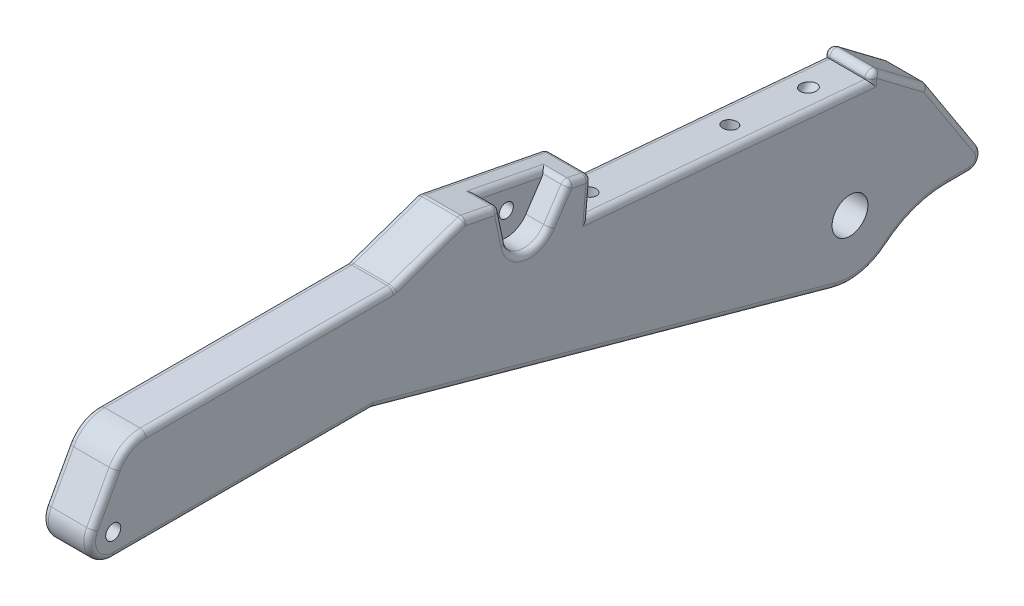
SolidWorks part; units mm, degrees
ref_plane "Front Plane" through (0, 0, 0) normal (0, 0, 1) x (1, 0, 0)
ref_plane "Top Plane" through (0, 0, 0) normal (0, 1, 0) x (1, 0, 0)
ref_plane "Right Plane" through (0, 0, 0) normal (1, 0, 0) x (0, 0, -1)
sketch "Sketch1" plane through (0, 0, 0) normal (1, 0, 0) x (0, 0, -1)
  line L0 (-5.5746, 3.0408) -> (3.158, 19.05)
  line L1 (3.158, 19.05) -> (75.6627, 19.05)
  line L3 (129.0542, 18.9233) -> (128.2241, 9.4345)
  line L4 (128.2241, 9.4345) -> (204.1341, 2.7933)
  line L6 (0, -6.35) -> (69.85, -6.35)
  line L8 (-5.5746, 3.0408) -> (7.9306, 27.7995) construction
  line L9 (129.0542, 18.9233) -> (94.7762, 25.6144)
  line L10 (94.7762, 25.6144) -> (75.6627, 19.05)
  line L12 (70.0006, 30.4506) -> (127.6524, 19.1969) construction
  line L15 (128.3624, 11.016) -> (128.9159, 17.3418) construction
  line L24 (219.6164, -5.5196) -> (233.4447, -26.8477) construction
  line L26 (219.7687, -5.7545) -> (233.4447, -26.8477)
  line L29 (69.85, 30.48) -> (129.0542, 18.9233) construction
  line L30 (206.6988, 4.2294) -> (219.393, -5.351) construction
  line L31 (204.1341, 2.7933) -> (204.161, 3.1007) construction
  line L32 (230.7807, -31.75) -> (224.8967, -31.75) construction
  line L33 (194.299, -40.7027) -> (69.85, -6.35) construction
  line L34 (206.6988, 4.2294) -> (219.393, -5.351)
  line L35 (204.1341, 2.7933) -> (204.161, 3.1007)
  line L36 (230.7807, -31.75) -> (224.8967, -31.75)
  line L37 (194.299, -40.7027) -> (69.85, -6.35)
  line L39 (-5.5746, 3.0408) -> (7.9306, 27.7995) construction
  circle A0 centre (0, 0) radius 2.032
  arc A1 (-5.5746, 3.0408) -> (0, -6.35) centre (0, 0) ccw
  arc A3 (0, -6.35) -> (-5.5746, 3.0408) centre (0, 0) ccw construction
  arc A12 (230.7807, -31.75) -> (233.4447, -26.8477) centre (230.7807, -28.575) ccw construction
  arc A13 (230.7807, -31.75) -> (233.4447, -26.8477) centre (230.7807, -28.575) ccw
  arc A14 (206.6988, 4.2294) -> (204.161, 3.1007) centre (205.7425, 2.9623) ccw construction
  arc A15 (224.8967, -31.75) -> (208.6668, -37.6115) centre (224.8967, -57.15) ccw construction
  arc A16 (194.299, -40.7027) -> (208.6668, -37.6115) centre (198.5232, -25.4) ccw construction
  arc A17 (206.6988, 4.2294) -> (204.161, 3.1007) centre (205.7425, 2.9623) ccw
  arc A18 (224.8967, -31.75) -> (208.6668, -37.6115) centre (224.8967, -57.15) ccw
  arc A19 (194.299, -40.7027) -> (208.6668, -37.6115) centre (198.5232, -25.4) ccw
  arc A20 (219.7687, -5.7545) -> (219.393, -5.351) centre (218.4366, -6.6181) ccw construction
  arc A21 (219.7687, -5.7545) -> (219.393, -5.351) centre (218.4366, -6.6181) ccw
  dimension "D1" = 4.064
  dimension "D2" = 19.05
  dimension "D3" = 30
  dimension "D4" = 34.925
extrude "Boss-Extrude1" add sketch "Sketch1" along normal blind 12.7
fillet "Fillet1" radius 9.525 1 edges at (6.35, 19.05, -3.158)
sketch "Sketch2" plane through (0, 0, 0) normal (-1, 0, 0) x (0, 0, 1)
  circle A0 centre (-198.5232, -25.4) radius 4.826
  circle A3 centre (-198.5232, -25.4) radius 5.715 construction
  dimension "D1" = 9.652
extrude "Cut-Extrude1" cut sketch "Sketch2" against normal through all
sketch "Sketch9" plane through (12.7, 0, 0) normal (1, 0, 0) x (0, 0, -1)
  line L0 (106.0359, 14.4582) -> (104.1247, 23.7895)
  line L2 (117.5418, 12.2123) -> (122.8219, 20.1398)
  line L3 (104.1247, 23.7895) -> (122.8219, 20.1398)
  line L4 (129.0542, 18.9233) -> (94.7762, 25.6144) construction
  arc A0 (106.0359, 14.4582) -> (117.5418, 12.2123) centre (112.2567, 15.7323) ccw
  dimension "D1" = 12.7
  dimension "D2" = 6.35
  dimension "D3" = 19.05
extrude "Cut-Extrude6" cut sketch "Sketch9" against normal blind 6.35
sketch "Sketch10" plane through (6.35, 0, 0) normal (1, 0, 0) x (0, 0, -1)
  circle A0 centre (112.2567, 15.7323) radius 1.905
  arc A1 (106.0359, 14.4582) -> (117.5418, 12.2123) centre (112.2567, 15.7323) ccw construction
  dimension "D1" = 3.81
extrude "Cut-Extrude7" cut sketch "Sketch10" against normal through all
sketch "Sketch4" plane through (0, 0, 0) normal (1, 0, 0) x (0, 0, -1)
  circle A0 centre (198.5232, -25.4) radius 5.715
  dimension "D1" = 11.43
extrude "Cut-Extrude2" cut sketch "Sketch4" along normal blind 1.5875
fillet "Fillet2" radius 1.5875 48 edges at (0, 2.947, -204.1476) (0, 4.4128, -205.0973) (0, -0.5608, -213.0459) (0, -5.5363, -219.5985) (0, -16.3011, -226.6067) (0, -30.091, -233.5704) (0, -31.75, -227.8387) (0, -33.2603, -216.2687) (0, -40.9199, -201.8622) (0, -6.35, -34.925) (0, -3.2414, 5.4604) (0, 8.5635, 2.5621) (0, 17.7156, -3.9501) (12.7, 2.947, -204.1476) (12.7, 4.4128, -205.0973) (12.7, -0.5608, -213.0459) (12.7, -5.5363, -219.5985) (12.7, -16.3011, -226.6067) (12.7, -30.091, -233.5704) (12.7, -31.75, -227.8387) (12.7, -33.2603, -216.2687) (12.7, -40.9199, -201.8622) (12.7, -6.35, -34.925) (12.7, -3.2414, 5.4604) (12.7, 8.5635, 2.5621) (12.7, 17.7156, -3.9501) (0, -23.5263, -132.0745) (0, 6.1139, -166.1791) (0, 14.1789, -128.6392) (0, 19.05, -42.2375) (12.7, -23.5263, -132.0745) (12.7, 6.1139, -166.1791) (12.7, 14.1789, -128.6392) (12.7, 19.05, -42.2375) (12.7, 19.1239, -105.0803) (12.7, 16.1761, -120.1818) (12.7, 9.4999, -111.0402) (12.7, 19.5316, -125.938) (0, 22.2688, -111.9152) (9.525, 20.1398, -122.8219) (9.525, 23.7895, -104.1247) (6.35, 21.9647, -113.4733) (12.7, 24.702, -99.4505) (12.7, 22.3322, -85.2195) (0, 22.3322, -85.2195) (6.35, 25.6144, -94.7762) (6.35, 19.05, -75.6627) (6.35, 18.9233, -129.0542)
sketch "Sketch6" plane through (0, 102.0823, -77.0424) normal (0, 0.7982, -0.6024) x (1, 0, 0)
  circle A0 centre (6.35, 152.3647) radius 1.905
  circle A1 centre (6.35, 152.3647) radius 2.286 construction
  dimension "D1" = 3.81
extrude "Cut-Extrude3" cut sketch "Sketch6" against normal blind 25.4
sketch "Sketch7" plane through (0, 20.4958, -1.7931) normal (0, 0.9962, -0.0872) x (1, 0, 0)
  circle A0 centre (6.35, 171.3639) radius 1.905
  circle A1 centre (6.35, 133.2639) radius 1.905
  circle A2 centre (6.35, 133.2639) radius 2.286 construction
  circle A3 centre (6.35, 171.3639) radius 2.286 construction
  dimension "D1" = 3.81
extrude "Cut-Extrude4" cut sketch "Sketch7" against normal blind 15.875
sketch "Sketch8" plane through (0, 98.6153, -152.0993) normal (0, 0.544, -0.8391) x (-1, 0, 0)
  circle A0 centre (-6.35, -139.9823) radius 1.905
  circle A1 centre (-6.35, -139.9823) radius 2.286 construction
  dimension "D1" = 3.81
extrude "Cut-Extrude5" cut sketch "Sketch8" against normal blind 12.7
